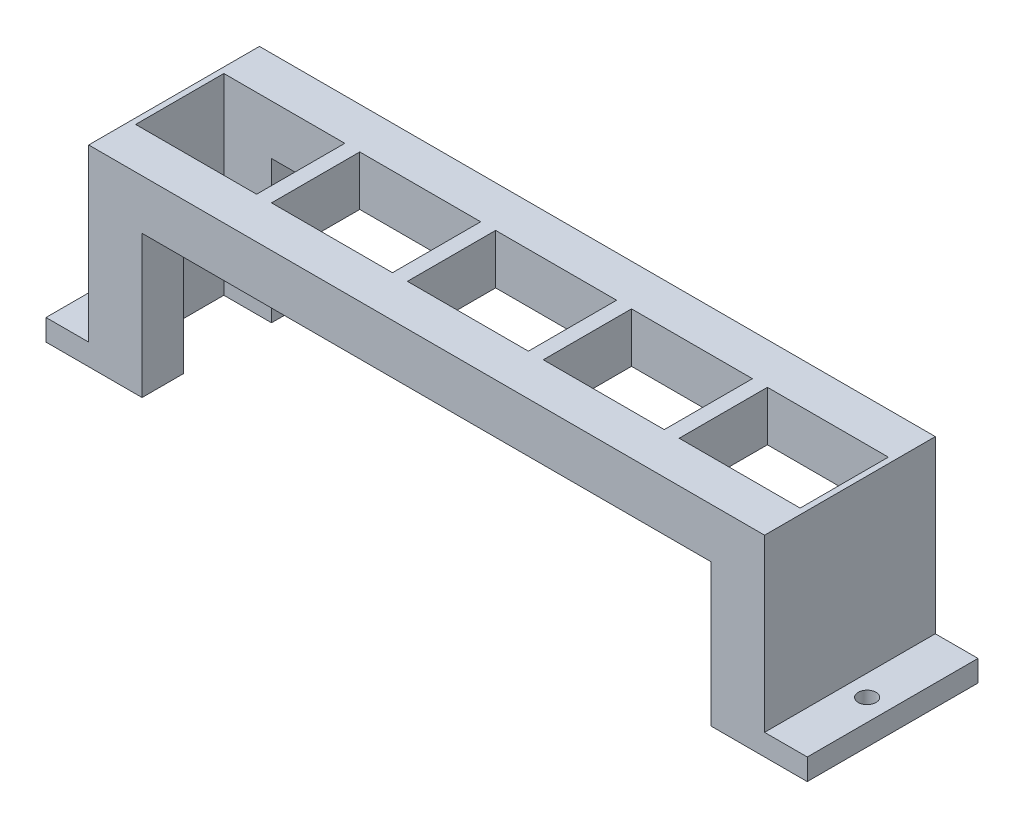
SolidWorks part; units mm, degrees
ref_plane "Front Plane" through (0, 0, 0) normal (0, 0, 1) x (1, 0, 0)
ref_plane "Top Plane" through (0, 0, 0) normal (0, 1, 0) x (1, 0, 0)
ref_plane "Right Plane" through (0, 0, 0) normal (1, 0, 0) x (0, 0, -1)
sketch "Sketch1" plane through (0, 0, 0) normal (0, 1, 0) x (1, 0, 0)
  line L1 (-47.5, -12) -> (47.5, -12)
  line L2 (-47.5, -12) -> (-47.5, 12)
  line L3 (-47.5, 12) -> (47.5, 12)
  line L4 (47.5, -12) -> (47.5, 12)
  line L5 (-47.5, -12) -> (47.5, 12) construction
  line L6 (-47.5, 12) -> (47.5, -12) construction
  point P0 (0, 0)
  dimension "D1" = 24
  dimension "95" = 95
extrude "Boss-Extrude1" add sketch "Sketch1" along normal blind 27
sketch "Sketch2" plane through (0, 27, 0) normal (0, 1, 0) x (1, 0, 0)
  line L0 (10.6, 6.2) -> (27.6, 6.2)
  line L1 (-8.5, 6.2) -> (8.5, 6.2)
  line L2 (-8.5, 6.2) -> (-8.5, -6.2)
  line L3 (-8.5, -6.2) -> (8.5, -6.2)
  line L4 (8.5, 6.2) -> (8.5, -6.2)
  line L5 (-8.5, 6.2) -> (8.5, -6.2) construction
  line L6 (-8.5, -6.2) -> (8.5, 6.2) construction
  line L7 (10.6, 6.2) -> (10.6, -6.2)
  line L8 (10.6, -6.2) -> (27.6, -6.2)
  line L9 (27.6, 6.2) -> (27.6, -6.2)
  line L10 (10.6, 6.2) -> (27.6, -6.2) construction
  line L11 (10.6, -6.2) -> (27.6, 6.2) construction
  line L12 (-27.6, 6.2) -> (-10.6, 6.2)
  line L13 (-27.6, 6.2) -> (-27.6, -6.2)
  line L14 (-27.6, -6.2) -> (-10.6, -6.2)
  line L15 (-10.6, 6.2) -> (-10.6, -6.2)
  line L16 (-27.6, 6.2) -> (-10.6, -6.2) construction
  line L17 (-27.6, -6.2) -> (-10.6, 6.2) construction
  line L18 (-46.7, 6.2) -> (-29.7, 6.2)
  line L19 (-46.7, 6.2) -> (-46.7, -6.2)
  line L20 (-46.7, -6.2) -> (-29.7, -6.2)
  line L21 (-29.7, 6.2) -> (-29.7, -6.2)
  line L22 (-46.7, 6.2) -> (-29.7, -6.2) construction
  line L23 (-46.7, -6.2) -> (-29.7, 6.2) construction
  line L24 (29.7, 6.2) -> (46.7, 6.2)
  line L25 (29.7, 6.2) -> (29.7, -6.2)
  line L26 (29.7, -6.2) -> (46.7, -6.2)
  line L27 (46.7, 6.2) -> (46.7, -6.2)
  line L28 (29.7, 6.2) -> (46.7, -6.2) construction
  line L29 (29.7, -6.2) -> (46.7, 6.2) construction
  line L30 (-29.7, 6.2) -> (-27.6, 6.2) construction
  line L31 (-10.6, 6.2) -> (-8.5, 6.2) construction
  line L32 (8.5, 6.2) -> (10.6, 6.2) construction
  line L33 (27.6, 6.2) -> (29.7, 6.2) construction
  point P5 (0, 0)
  point P6 (0, 0)
  point P11 (19.1, 0)
  point P12 (19.1, 0)
  point P17 (-19.1, 0)
  point P18 (-19.1, 0)
  point P23 (-38.2, 0)
  point P24 (-38.2, 0)
  point P29 (38.2, 0)
  point P30 (38.2, 0)
  dimension "D1" = 17
  dimension "D2" = 12.4
  dimension "D3" = 2.1
extrude "Cut-Extrude1" cut sketch "Sketch2" against normal through all
sketch "Sketch3" plane through (0, 0, 0) normal (0, -1, 0) x (1, 0, 0)
  line L1 (40, 22.0342) -> (-40, 22.0342)
  line L2 (40, 22.0342) -> (40, -22.0342)
  line L3 (40, -22.0342) -> (-40, -22.0342)
  line L4 (-40, 22.0342) -> (-40, -22.0342)
  line L5 (40, 22.0342) -> (-40, -22.0342) construction
  line L6 (40, -22.0342) -> (-40, 22.0342) construction
  point P0 (0, 0)
  dimension "D1" = 80
extrude "Cut-Extrude2" cut sketch "Sketch3" along direction (0, -1, 0) on the side against the normal blind 20
sketch "Sketch4" plane through (47.5, 0, 0) normal (1, 0, 0) x (0, 0, -1)
  line L0 (12, 27) -> (12, 0) construction
  line L1 (-12, 0) -> (12, 0)
  line L2 (-12, 0) -> (-12, 3)
  line L3 (-12, 3) -> (12, 3)
  line L4 (12, 0) -> (12, 3)
  dimension "3" = 3
extrude "Boss-Extrude2" add sketch "Sketch4" along normal blind 6
sketch "Sketch5" plane through (-47.5, 0, 0) normal (-1, 0, 0) x (0, 0, 1)
  line L0 (-12, 27) -> (-12, 0) construction
  line L1 (12, 0) -> (-12, 0)
  line L2 (12, 0) -> (12, 3)
  line L3 (12, 3) -> (-12, 3)
  line L4 (-12, 0) -> (-12, 3)
  dimension "D1" = 3
extrude "Boss-Extrude3" add sketch "Sketch5" along normal blind 6
sketch "Sketch6" plane through (0, 3, 0) normal (0, 1, 0) x (1, 0, 0)
  circle A0 centre (50.4535, -0.5379) radius 1.25
  dimension "D1" = 2.5
extrude "Cut-Extrude3" cut sketch "Sketch6" against normal through all
sketch "Sketch7" plane through (0, 3, 0) normal (0, 1, 0) x (1, 0, 0)
  circle A0 centre (-50.9108, 0.4367) radius 1.25
  dimension "D1" = 2.5
extrude "Cut-Extrude4" cut sketch "Sketch7" against normal through all
